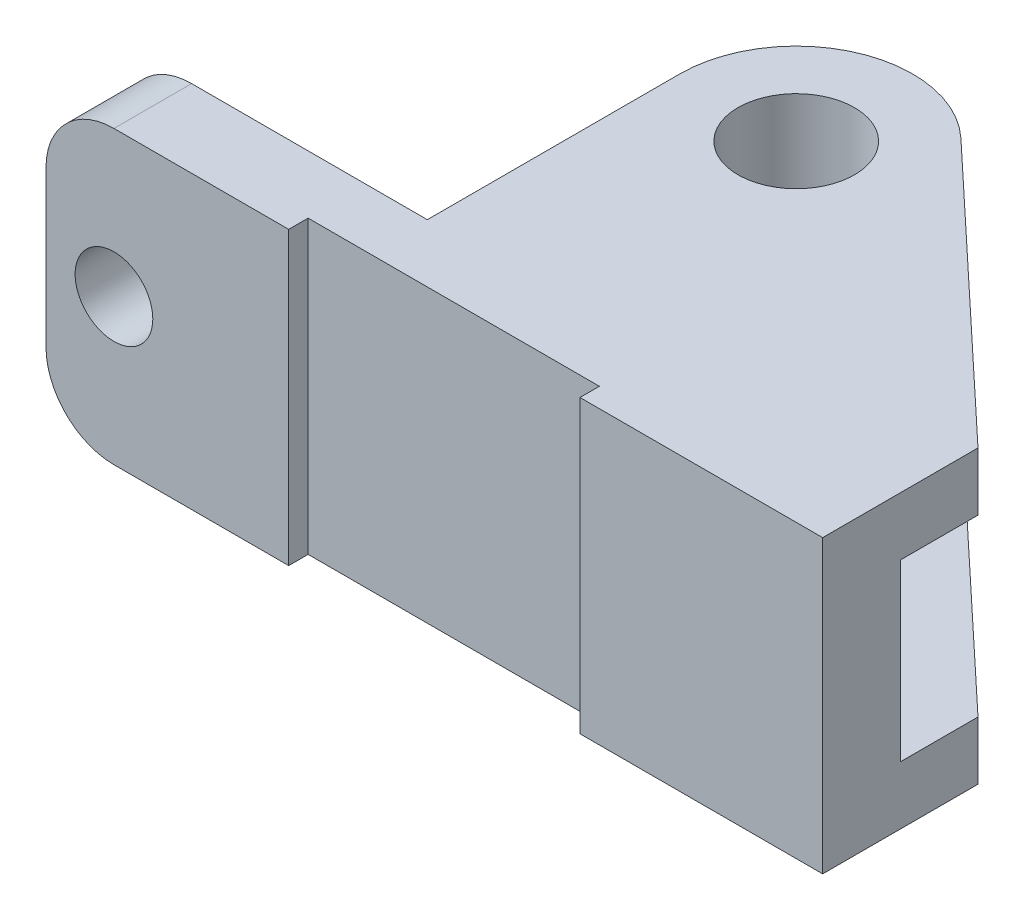
SolidWorks part; units mm, degrees
ref_plane "Front Plane" through (0, 0, 0) normal (0, 0, 1) x (1, 0, 0)
ref_plane "Top Plane" through (0, 0, 0) normal (0, 1, 0) x (1, 0, 0)
ref_plane "Right Plane" through (0, 0, 0) normal (1, 0, 0) x (0, 0, -1)
sketch "Sketch1" plane through (0, 0, 0) normal (0, 0, 1) x (1, 0, 0)
  line L1 (-33, -15) -> (40, -15)
  line L2 (-40, -8) -> (-40, 8)
  line L3 (-33, 15) -> (40, 15)
  line L4 (40, -15) -> (40, 15)
  line L5 (-40, -15) -> (40, 15) construction
  line L6 (-40, 15) -> (40, -15) construction
  arc A0 (-40, 8) -> (-33, 15) centre (-33, 8) cw
  arc A1 (-33, -15) -> (-40, -8) centre (-33, -8) cw
  point P0 (0, 0)
  dimension "D3" = 7
  dimension "D1" = 80
  dimension "D2" = 30
extrude "Boss-Extrude1" add sketch "Sketch1" along normal blind 8
sketch "Sketch2" plane through (0, 0, 8) normal (0, 0, 1) x (1, 0, 0)
  line L0 (-40, 8) -> (-40, -8) construction
  circle A0 centre (-33, 0) radius 4
  dimension "D1" = 8
  dimension "D2" = 7
extrude "Cut-Extrude1" cut sketch "Sketch2" against normal through all
sketch "Sketch3" plane through (0, 15, 0) normal (0, 1, 0) x (1, 0, 0)
  line L0 (40, 0) -> (40, 8)
  line L1 (40, 8) -> (11.4879, 34.7512)
  line L3 (-8.7228, 26) -> (-8.7228, 0)
  line L4 (40, 0) -> (-33, 0) construction
  line L5 (-8.7228, 0) -> (40, 0)
  line L6 (-8.7228, 26) -> (20.8152, 26)
  line L7 (11.4879, 34.7512) -> (-8.7228, 26)
  circle A1 centre (3.2772, 26) radius 12 construction
  line M5 (40, 0) -> (-33, 0)
  dimension "D3" = 24
  dimension "D1" = 8
  dimension "D2" = 26
extrude "Boss-Extrude2" add sketch "Sketch3" against normal blind 6 contours L6 L3 L0 L1 M5 | L1 L7 L6
mirror "Mirror1" about plane through (0, 0, 0) normal (0, 1, 0) of "Boss-Extrude2"
sketch "Sketch5" plane through (0, 15, 0) normal (0, 1, 0) x (1, 0, 0)
  line L1 (-8.7228, 26) -> (3.2772, 26) construction
  line L2 (-8.7228, 26) -> (20.8152, 26) construction
  circle A1 centre (3.2772, 26) radius 12
  dimension "D1" = 12
extrude "Boss-Extrude3" add sketch "Sketch5" against normal through all
sketch "Sketch8" plane through (0, 15, 0) normal (0, 1, 0) x (1, 0, 0)
  circle A0 centre (3.2772, 26) radius 6
  dimension "D1" = 12
extrude "Cut-Extrude2" cut sketch "Sketch8" against normal through all
sketch "Sketch9" plane through (0, 15, 0) normal (0, 1, 0) x (1, 0, 0)
  line L0 (40, -8) -> (-33, -8) construction
  line L1 (-15, -8) -> (15, -8)
  line L2 (-15, -8) -> (-15, -6)
  line L3 (-15, -6) -> (15, -6)
  line L4 (15, -8) -> (15, -6)
  point P6 (0, -8)
  dimension "D1" = 30
  dimension "D2" = 2
extrude "Cut-Extrude3" cut sketch "Sketch9" against normal through all
